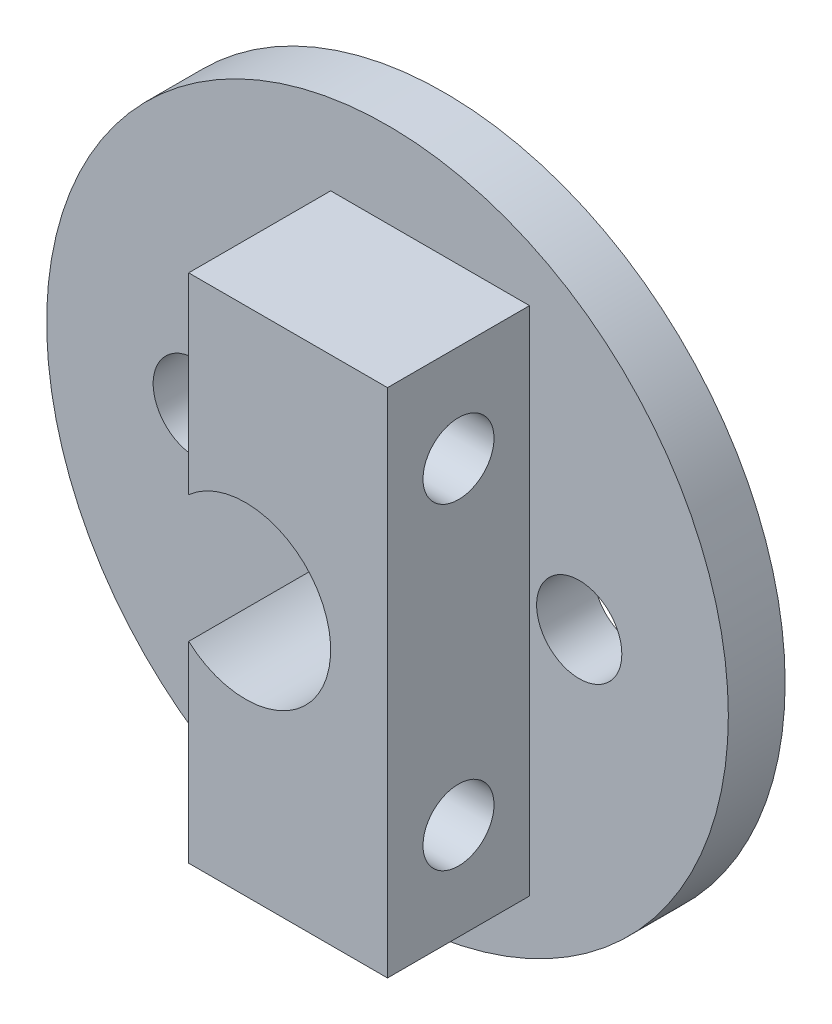
SolidWorks part; units mm, degrees
ref_plane "Plan de face" through (0, 0, 0) normal (0, 0, 1) x (1, 0, 0)
ref_plane "Plan de dessus" through (0, 0, 0) normal (0, 1, 0) x (1, 0, 0)
ref_plane "Plan de droite" through (0, 0, 0) normal (1, 0, 0) x (0, 0, -1)
sketch "Esquisse1" plane through (0, 0, 0) normal (0, 0, 1) x (1, 0, 0)
  line L0 (0, 12) -> (0, -12) construction
  line L1 (-12, 0) -> (12, 0) construction
  circle A0 centre (0, 0) radius 12
  circle A1 centre (-6.75, 0) radius 1.5
  circle A2 centre (6.75, 0) radius 1.5
  circle A3 centre (0, 0) radius 3
  dimension "D1" = 24
  dimension "D4" = 3
  dimension "D5" = 3
  dimension "D2" = 6.75
  dimension "D3" = 6.75
extrude "Boss.-Extru.1" add sketch "Esquisse1" along normal blind 2
sketch "Esquisse2" plane through (0, 0, 2) normal (0, 0, 1) x (1, 0, 0)
  line L0 (-2, -2.2361) -> (-2, -9)
  line L1 (-2, 9) -> (5, 9)
  line L2 (-2, 9) -> (-2, 2.2361)
  line L3 (-2, -9) -> (5, -9)
  line L4 (5, 9) -> (5, -9)
  arc A0 (-2, -2.2361) -> (-2, 2.2361) centre (0, 0) ccw
  dimension "D1" = 7
  dimension "D2" = 5
  dimension "D3" = 18
  dimension "D4" = 9
extrude "Boss.-Extru.2" add sketch "Esquisse2" along normal blind 5
sketch "Esquisse3" plane through (-2, 0, 0) normal (-1, 0, 0) x (0, 0, 1)
  line L0 (7, 0) -> (0, 0) construction
  line L1 (7, -3) -> (7, 3) construction
  line L2 (7, 9) -> (7, 2.2361) construction
  line L3 (7, 2.2361) -> (2, 2.2361) construction
  circle A0 centre (4.5, 5.5861) radius 1.25
  circle A1 centre (4.5, -5.5861) radius 1.25
  dimension "D1" = 2.5
  dimension "D2" = 2.5
  dimension "D3" = 3.35
extrude "Enlèv. mat.-Extru.1" cut sketch "Esquisse3" against normal through all
